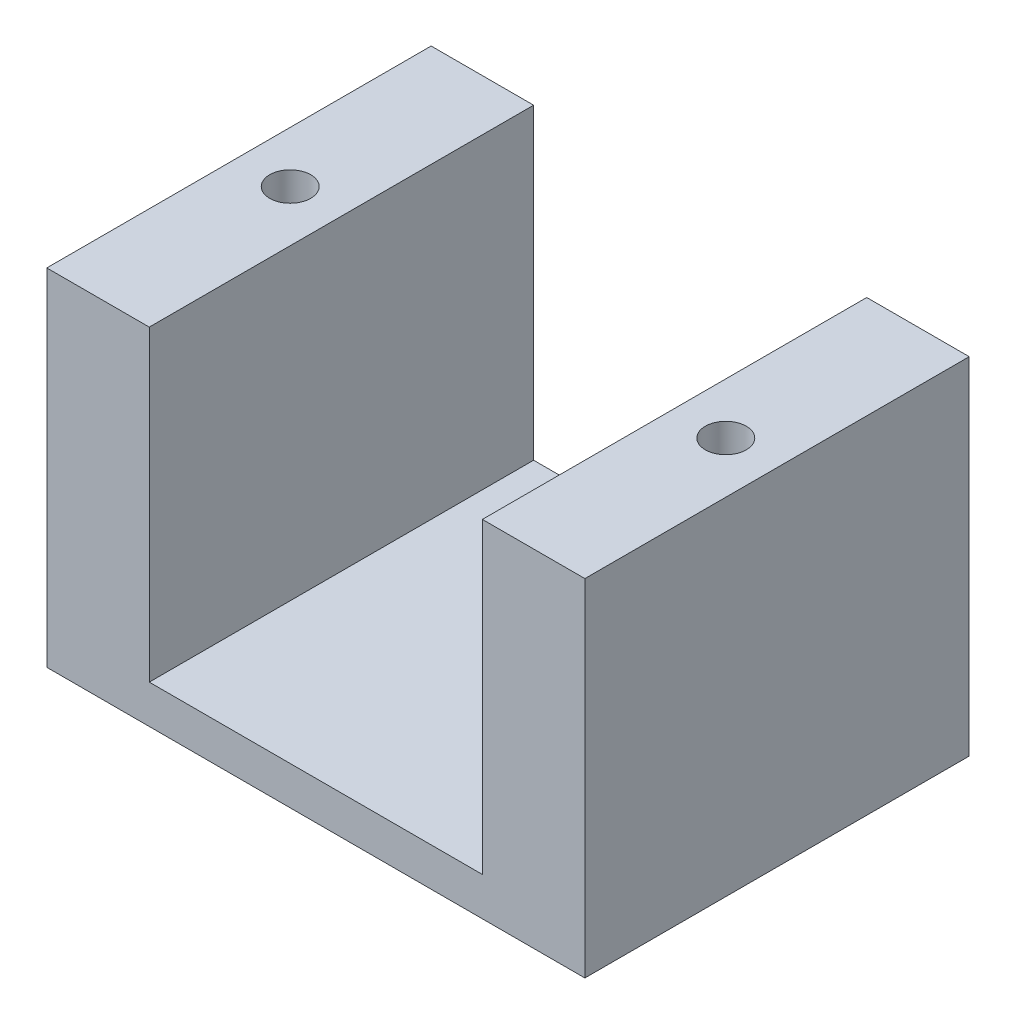
SolidWorks part; units mm, degrees
ref_plane "Alzado" through (0, 0, 0) normal (0, 0, 1) x (1, 0, 0)
ref_plane "Planta" through (0, 0, 0) normal (0, 1, 0) x (1, 0, 0)
ref_plane "Vista lateral" through (0, 0, 0) normal (1, 0, 0) x (0, 0, -1)
sketch "Croquis1" plane through (0, 0, 0) normal (0, 0, 1) x (1, 0, 0)
  line L0 (-21, 0) -> (-21, 27)
  line L1 (-21, 0) -> (21, 0)
  line L3 (-13, 3) -> (13, 3)
  line L5 (-21, 27) -> (-13, 27)
  line L6 (-13, 27) -> (-13, 3)
  line L7 (21, 0) -> (21, 27)
  line L8 (21, 27) -> (13, 27)
  line L9 (13, 27) -> (13, 3)
  point P4 (0, 0)
  dimension "D1" = 3
  dimension "D2" = 42
  dimension "D3" = 8
  dimension "D4" = 8
  dimension "D5" = 27
extrude "Saliente-Extruir1" add sketch "Croquis1" along normal blind 30
sketch "Croquis2" plane through (0, 0, 0) normal (0, -1, 0) x (1, 0, 0)
  line L0 (-21, 30) -> (-21, 0) construction
  line L1 (-21, 30) -> (21, 30) construction
  line L2 (-13, 30) -> (-13, 0) construction
  line L3 (0, 0) -> (0, 30) construction
  line L4 (-21, 0) -> (21, 0) construction
  line L5 (-21, 15) -> (-13, 15) construction
  circle A0 centre (-17, 15) radius 1.6
  circle A1 centre (17, 15) radius 1.6
  point P17 (-17, 15)
  dimension "D2" = 3.2
  dimension "D1" = 8
extrude "Cortar-Extruir1" cut sketch "Croquis2" against normal blind 41 and the other way blind 15
sketch "Croquis3" plane through (0, 0, 0) normal (0, -1, 0) x (1, 0, 0)
  line L0 (0, 0) -> (0, 30) construction
  line L1 (-21, 30) -> (21, 30) construction
  circle A0 centre (-17, 15) radius 2.9
  circle A1 centre (17, 15) radius 2.9
  dimension "D1" = 5.8
extrude "Cortar-Extruir2" cut sketch "Croquis3" against normal blind 3.2
sketch "Sketch1" plane through (0, 0, 0) normal (0, -1, 0) x (1, 0, 0)
  line L0 (-5.936, 6.4386) -> (9.6782, 6.4386)
  line L1 (-7.0605, 7.6292) -> (-7.0605, 16.2252)
  line L2 (-5.4679, 16.2252) -> (-5.4679, 9.0826)
  line L3 (-4.4622, 8.0736) -> (7.9314, 8.0736)
  line L4 (8.8676, 9.0826) -> (8.8676, 19.869)
  line L5 (9.0046, 22.1062) -> (9.6782, 22.1062)
  line L6 (10.5367, 20.9571) -> (10.5367, 7.2279)
  line L7 (-1.522, 11.058) -> (-3.3045, 9.8834)
  line L8 (-3.3045, 9.8834) -> (-3.9573, 10.5323)
  line L9 (-3.9573, 10.5323) -> (-2.6966, 12.2819)
  line L10 (-1.1994, 11.7943) -> (0.6787, 13.6971)
  line L11 (0.6787, 13.6971) -> (-0.0721, 14.4381)
  line L12 (-1.9011, 12.6091) -> (-0.0721, 14.4381)
  line L13 (-0.3544, 15.3902) -> (5.4126, 9.6983)
  line L14 (6.9772, 11.7943) -> (1.3034, 17.4681)
  line L15 (-4.1231, 19.249) -> (-2.4051, 17.5533)
  line L16 (-2.4051, 17.5533) -> (-1.3661, 17.8452)
  line L17 (-1.3661, 17.8452) -> (-0.6946, 19.0415)
  line L18 (-0.6946, 19.0415) -> (-2.4282, 20.7525)
  line L19 (3.8921, 15.4583) -> (1.8919, 17.5869)
  line L20 (1.8919, 17.5869) -> (5.231, 20.9571)
  line L21 (3.8921, 15.4583) -> (7.2428, 18.7012)
  line L22 (3.839, 17.1631) -> (4.2591, 16.7469)
  line L23 (3.1023, 17.8931) -> (3.5224, 17.4768)
  line L24 (3.1023, 17.8931) -> (5.6053, 20.4195)
  line L25 (3.5224, 17.4768) -> (6.0255, 20.0032)
  line L26 (6.0255, 20.0032) -> (5.6053, 20.4195)
  line L27 (3.839, 17.1631) -> (6.3421, 19.6896)
  line L28 (6.3421, 19.6896) -> (6.7622, 19.2733)
  line L29 (6.7622, 19.2733) -> (4.2591, 16.7469)
  circle A0 centre (6.1388, 10.7766) radius 0.6615
  spline S0 degree 3 poles (-5.936, 6.4386) (-6.8115, 6.3822) (-7.0966, 6.7007) (-7.0605, 7.6292) knots 0 0 0 0 1 1 1 1
  spline S1 degree 3 poles (-7.0605, 16.2252) (-7.0333, 16.7381) (-6.9457, 17.0411) (-6.2273, 16.9641) knots 0 0 0 0 1 1 1 1
  spline S2 degree 3 poles (-6.2273, 16.9641) (-5.68, 16.9641) (-5.4679, 16.7195) (-5.4679, 16.2252) knots 0 0 0 0 1 1 1 1
  spline S3 degree 3 poles (-5.4679, 9.0826) (-5.4337, 8.45) (-5.3084, 8.0736) (-4.4622, 8.0736) knots 0 0 0 0 1 1 1 1
  spline S4 degree 3 poles (7.9314, 8.0736) (8.5995, 8.1022) (8.8676, 8.3299) (8.8676, 9.0826) knots 0 0 0 0 1 1 1 1
  spline S5 degree 2 poles (8.8676, 19.869) (8.8786, 20.4868) (8.3125, 20.6309) knots 0 0 0 1 1 1
  spline S6 degree 3 poles (8.3125, 20.6309) (8.286, 22.1282) (8.3383, 22.1062) (9.0046, 22.1062) knots 0 0 0 0 1 1 1 1
  spline S7 degree 3 poles (9.6782, 22.1062) (10.1625, 22.0732) (10.5367, 21.6954) (10.5367, 20.9571) knots 0 0 0 0 1 1 1 1
  spline S8 degree 2 poles (9.6782, 6.4386) (10.5243, 6.4531) (10.5367, 7.2279) knots 0 0 0 1 1 1
  spline S9 degree 3 poles (-7.0996, 18.3089) (-6.9442, 19.7996) (-5.7568, 20.9901) (-4.0111, 21.1662) knots 0 0 0 0 1 1 1 1
  spline S10 degree 2 poles (-7.0996, 18.3089) (-7.1835, 17.9149) (-7.614, 17.9271) knots 0 0 0 1 1 1
  spline S11 degree 2 poles (-7.614, 17.9271) (-8.1227, 17.9757) (-8.0635, 18.7012) knots 0 0 0 1 1 1
  spline S12 degree 3 poles (-4.0111, 21.1662) (-3.8331, 21.1909) (-3.6419, 21.3753) (-3.6249, 21.6078) knots 0 0 0 0 1 1 1 1
  spline S13 degree 3 poles (-3.6249, 21.6078) (-3.6395, 21.8931) (-3.8847, 22.1736) (-4.1959, 22.144) knots 0 0 0 0 1 1 1 1
  spline S14 degree 3 poles (-8.0635, 18.7012) (-7.7251, 20.5144) (-5.9748, 22.0835) (-4.1959, 22.144) knots 0 0 0 0 1 1 1 1
  spline S15 degree 3 poles (-9.3191, 18.4114) (-9.3331, 19.5601) (-7.8959, 23.2191) (-3.9573, 23.3255) knots 0 0 0 0 1 1 1 1
  spline S16 degree 2 poles (-9.3191, 18.4114) (-9.3752, 17.9149) (-9.8057, 17.9271) knots 0 0 0 1 1 1
  spline S17 degree 2 poles (-9.8057, 17.9271) (-10.3143, 17.9757) (-10.2437, 18.7012) knots 0 0 0 1 1 1
  spline S18 degree 3 poles (-3.9573, 23.3255) (-3.7793, 23.3502) (-3.5979, 23.5957) (-3.6249, 23.7765) knots 0 0 0 0 1 1 1 1
  spline S19 degree 3 poles (-3.6249, 23.7765) (-3.6395, 24.0618) (-3.8847, 24.3171) (-4.1959, 24.2875) knots 0 0 0 0 1 1 1 1
  spline S20 degree 3 poles (-10.2437, 18.7012) (-10.1828, 20.3463) (-8.41, 24.0442) (-4.1959, 24.2875) knots 0 0 0 0 1 1 1 1
  spline S21 degree 3 poles (-11.5231, 18.3954) (-11.0409, 22.6123) (-7.9005, 25.4412) (-3.9618, 25.5476) knots 0 0 0 0 1 1 1 1
  spline S22 degree 2 poles (-11.5231, 18.3954) (-11.5793, 17.8989) (-12.0098, 17.9111) knots 0 0 0 1 1 1
  spline S23 degree 2 poles (-12.0098, 17.9111) (-12.5184, 17.9597) (-12.4477, 18.6852) knots 0 0 0 1 1 1
  spline S24 degree 3 poles (-3.9618, 25.5476) (-3.7839, 25.5723) (-3.6024, 25.8178) (-3.6295, 25.9986) knots 0 0 0 0 1 1 1 1
  spline S25 degree 3 poles (-3.6295, 25.9986) (-3.644, 26.2839) (-3.8893, 26.5392) (-4.2005, 26.5096) knots 0 0 0 0 1 1 1 1
  spline S26 degree 3 poles (-12.4477, 18.6852) (-12.3869, 20.3303) (-10.6378, 26.0828) (-4.2005, 26.5096) knots 0 0 0 0 1 1 1 1
  spline S27 degree 2 poles (-2.6966, 12.2819) (-2.2964, 12.3089) (-1.9011, 12.6091) knots 0 0 0 1 1 1
  spline S28 degree 3 poles (-1.522, 11.058) (-1.5267, 11.365) (-1.4007, 11.5904) (-1.1994, 11.7943) knots 0 0 0 0 1 1 1 1
  spline S29 degree 3 poles (-0.3544, 15.3902) (-3.4002, 14.6297) (-5.1424, 17.1196) (-4.1231, 19.249) knots 0 0 0 0 1 1 1 1
  spline S30 degree 3 poles (1.3034, 17.4681) (1.9117, 20.5405) (-1.1027, 21.5749) (-2.4282, 20.7525) knots 0 0 0 0 1 1 1 1
  spline S31 degree 3 poles (5.4126, 9.6983) (5.9288, 9.3021) (6.7006, 9.3911) (7.1257, 9.8834) knots 0 0 0 0 1 1 1 1
  spline S32 degree 2 poles (7.1257, 9.8834) (7.9343, 10.7999) (6.9772, 11.7943) knots 0 0 0 1 1 1
  spline S33 degree 2 poles (7.2428, 18.7012) (8.0732, 19.5689) (7.2696, 20.5232) knots 0 0 0 1 1 1
  spline S34 degree 3 poles (5.231, 20.9571) (5.5555, 21.3099) (6.6602, 21.3641) (7.2696, 20.5232) knots 0 0 0 0 1 1 1 1
extrude "Cut-Extrude1" cut sketch "Sketch1" against normal blind 0.4
